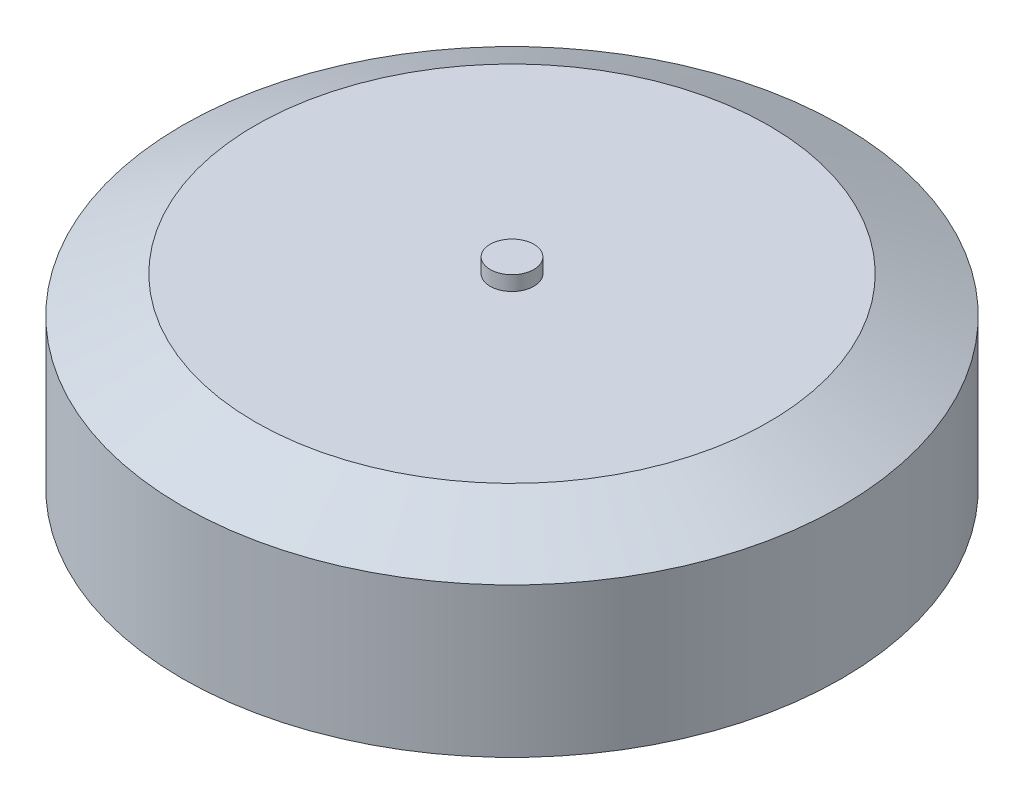
SolidWorks part; units mm, degrees
ref_plane "Plan de face" through (0, 0, 0) normal (0, 0, 1) x (1, 0, 0)
ref_plane "Plan de dessus" through (0, 0, 0) normal (0, 1, 0) x (1, 0, 0)
ref_plane "Plan de droite" through (0, 0, 0) normal (1, 0, 0) x (0, 0, -1)
sketch "Esquisse1" plane through (0, 0, 0) normal (0, 0, 1) x (1, 0, 0)
  line L0 (0, -78.3816) -> (0, 78.3816) construction
  line L1 (142.9419, 0) -> (-142.9419, 0) construction
  line L2 (0, 15.25) -> (-35.25, 15.25)
  line L3 (-35.25, 15.25) -> (-45.25, 10.25)
  line L4 (-45.25, 10.25) -> (-45.25, -10.25)
  line L5 (-45.25, -10.25) -> (-35.25, -15.25)
  line L6 (-35.25, -15.25) -> (0, -15.25)
  line L7 (0, 15.25) -> (0, -15.25)
  point P4 (0, 0)
  point P8 (0, 0)
  point P10 (-45.25, 0)
  dimension "D1" = 45.25
  dimension "D2" = 35.25
  dimension "D3" = 30.5
  dimension "D4" = 5
revolve "Révolution1" add sketch "Esquisse1" angle 360 about L0
sketch "Esquisse2" plane through (0, 15.25, 0) normal (0, 1, 0) x (1, 0, 0)
  circle A0 centre (0, 0) radius 3
  dimension "D1" = 6
extrude "Boss.-Extru.1" add sketch "Esquisse2" along normal blind 2
equation "\"D1@Esquisse1\"=90.5/2"
equation "\"D2@Esquisse1\"=\"D1@Esquisse1\"-10"
